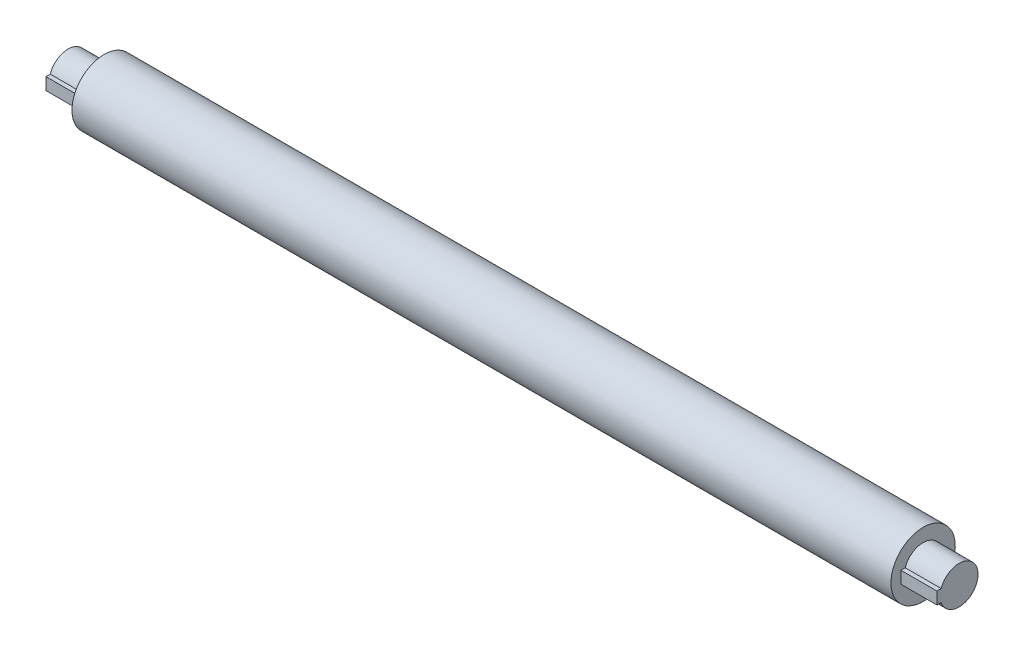
SolidWorks part; units mm, degrees
ref_plane "Front Plane" through (0, 0, 0) normal (0, 0, 1) x (1, 0, 0)
ref_plane "Top Plane" through (0, 0, 0) normal (0, 1, 0) x (1, 0, 0)
ref_plane "Right Plane" through (0, 0, 0) normal (1, 0, 0) x (0, 0, -1)
sketch "Sketch1" plane through (0, 0, 0) normal (0, 0, 1) x (1, 0, 0)
  line L0 (-588.665, 0) -> (-588.665, 25)
  line L1 (-588.665, 25) -> (-541.145, 25)
  line L2 (-541.145, 25) -> (-541.145, 42.5)
  line L3 (-541.145, 42.5) -> (541.145, 42.5)
  line L4 (541.145, 42.5) -> (541.145, 25)
  line L5 (541.145, 25) -> (588.665, 25)
  line L6 (588.665, 25) -> (588.665, 0)
  line L7 (588.665, 0) -> (-588.665, 0)
  dimension "D1" = 1177.33
  dimension "D2" = 47.52
  dimension "D3" = 47.52
  dimension "D4" = 25
  dimension "D5" = 42.5
  dimension "D6" = 25
  dimension "D7" = 588.665
revolve "Revolve1" add sketch "Sketch1" angle 360 about L7
ref_plane "Plane1" through (0, 0, 29.3) normal (0, 0, 1) x (1, 0, 0)
sketch "Sketch3" plane through (0, 0, 29.3) normal (0, 0, 1) x (1, 0, 0)
  line L0 (-588.665, 25) -> (-588.665, -25) construction
  line L1 (-588.665, 8) -> (-541.145, 8)
  line L2 (-588.665, 8) -> (-588.665, -8)
  line L3 (-588.665, -8) -> (-541.145, -8)
  line L4 (-541.145, 8) -> (-541.145, -8)
  line L5 (-541.145, 25) -> (-541.145, -25) construction
  line L6 (0, 89.5838) -> (0, -74.9794) construction
  line L7 (541.145, 8) -> (541.145, -8)
  line L8 (588.665, -8) -> (541.145, -8)
  line L9 (588.665, 8) -> (588.665, -8)
  line L10 (588.665, 8) -> (541.145, 8)
  dimension "D1" = 16
  dimension "D2" = 8
extrude "Boss-Extrude1" add sketch "Sketch3" against normal up to surface (5.6146 mm away)
